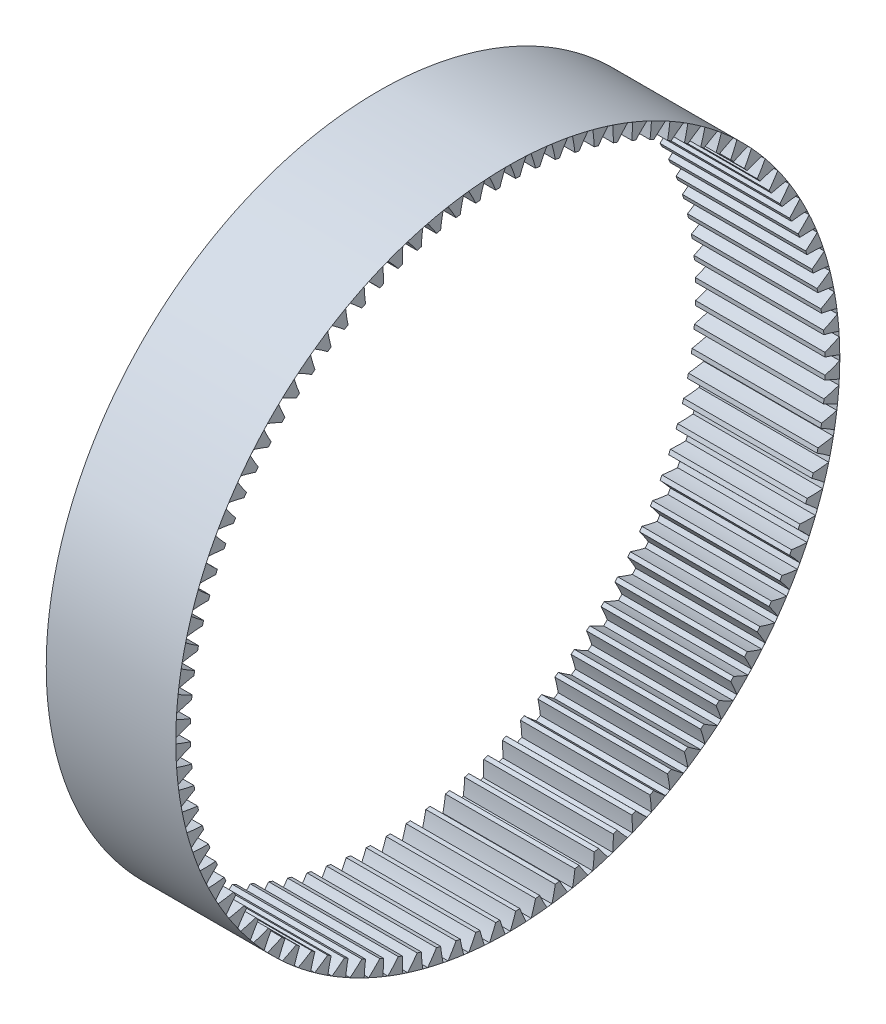
SolidWorks part; units mm, degrees
ref_plane "Plane1" through (0, 0, 0) normal (0, 0, 1) x (1, 0, 0)
ref_plane "Plane2" through (0, 0, 0) normal (0, 1, 0) x (1, 0, 0)
ref_plane "Plane3" through (0, 0, 0) normal (1, 0, 0) x (0, 0, -1)
other "Configuration Table"
sketch "HoldingSke" plane through (0, 0, 0) normal (0, 1, 0) x (1, 0, 0)
  line L0 (0, 0) -> (-0.0579, -0.3283)
  line L1 (-15, 0) -> (100, 0) construction
  line L2 (0, 0) -> (-2.1039, 2.3779)
  line L3 (0, 0) -> (-11.863, 4.5341)
  line L4 (0, 0) -> (-1.4996, 8.5048)
  line L5 (0, 0) -> (-23.7986, -8.8762)
  line L6 (0, 0) -> (-10.5278, -7.1032)
  line L7 (-2.1039, 2.3779) -> (3.3635, 27.1825)
  line L8 (-76.2, 5.3779) -> (-54.61, 5.3779)
  line L9 (-71.009, 38.7566) -> (-53.1078, 45.2721)
  line L10 (-76.2, 71.12) -> (104.1128, 71.12)
  line L11 (0, 0) -> (-60, 0)
  line L12 (-76.2, 101.6) -> (-76.093, 101.6)
  line L13 (24.9733, 27.94) -> (52.9518, 28.4284)
  line L14 (24.9733, 27.94) -> (24.9743, 27.94)
  line L15 (24.9733, 27.94) -> (100.4006, 29.5858)
  circle A0 centre (0, 0) radius 12.5
  circle A1 centre (0, 0) radius 12.7
  circle A2 centre (0, 0) radius 12.7
  dimension "MHD" = 25.4
  dimension "Hub_dia" = 25.4
  dimension "Diameter" = 25
  dimension "Num_teeth" = 100
  dimension "Pitch" = 0.3333
  dimension "Overall_len" = 25.4
  dimension "Show_teeth" = 100
  dimension "Thickness" = 12.7
  dimension "OAL" = 25.4001
  dimension "T_dim" = 21.59
  dimension "Ap" = 20
  dimension "H" = 19.05
  dimension "Pitch_radius" = 180.3128
  dimension "Width" = 60
  dimension "Backlash" = 0.107
  dimension "Addendum_fac" = 1
  dimension "Dedendum_fac" = 1.25
  dimension "Clearance_fac" = 0.25
  dimension "Dedendum_add" = 0.001
  dimension "Module" = 3
sketch "BasProSke" plane through (0, 0, 0) normal (0, 1, 0) x (1, 0, 0)
  line L0 (-10, 0) -> (60, 0) construction
  line L1 (0, 147) -> (0, 153.7764)
  line L2 (0, 147) -> (60, 147)
  line L3 (60, 147) -> (60, 153.7764)
  line L4 (60, 153.7764) -> (0, 153.7764)
  dimension "Thickness" = 60
  dimension "Diameter" = 307.5528
  dimension "Inside_diameter" = 294
revolve "Base-Revolve" add sketch "BasProSke" angle 360 about L0
sketch "TooCutSke" plane through (0, 0, 0) normal (1, 0, 0) x (0, 0, -1)
  line L3 (2.6236, 149.9771) -> (2.6236, 53.6633) construction
  line L4 (0, 0) -> (0, 59.563) construction
  line L5 (0, 0) -> (-2.1462, 68.2938) construction
  line L6 (-68.0184, 124.7836) -> (33.8394, 127.9846) construction
  circle A0 centre (0, 0) radius 150 construction
  circle A1 centre (0, 0) radius 153.751 construction
  circle A2 centre (0, 0) radius 126.8585 construction
  circle A3 centre (0, 0) radius 146.9746 construction
  arc A4 (3.6374, 146.9296) -> (1.1636, 153.7466) centre (-68.0184, 124.7836) ccw
  arc A5 (3.6374, 146.9296) -> (-3.6374, 146.9296) centre (0, 0) ccw
  arc A6 (1.1636, 153.7466) -> (-1.1636, 153.7466) centre (0, 0) ccw
  arc A7 (-1.1636, 153.7466) -> (-3.6374, 146.9296) centre (68.0184, 124.7836) ccw
  dimension "Pitch_dia" = 300
  dimension "Base_dia" = 253.717
  dimension "Root_dia" = 307.502
  dimension "Overcut_dia" = 293.9492
  dimension "Flank_rad" = 75
  dimension "Half_ang" = 1.8
  dimension "Half_CT" = 2.6236
extrude "ToothCut" cut sketch "TooCutSke" along normal through all
fillet "Breaks" [suppressed] radius 0.3
fillet "RootFillets" [suppressed] radius 0.751
pattern_circular "TeethCuts" count 100 every 3.6 about axis through (-10, 0, 0) along (1, 0, 0) of "RootFillets", "Breaks", "ToothCut"
equation "' \"Module@HoldingSke\" = 6.35"
equation "' \"Num_teeth@HoldingSke\" = 24"
equation "' \"Ap@HoldingSke\" =  14.5"
equation "' \"Ap@HoldingSke\" = 14.5"
equation "' \"Width@HoldingSke\" = 12"
equation "' \"Diameter@HoldingSke\" = 8 * 25.4"
equation "' \"Show_teeth@HoldingSke\" = 100"
equation "' \"Backlash@HoldingSke\" = 0.009 * 25.4"
equation "' \"Addendum_fac@HoldingSke\" = 1.0"
equation "' \"Dedendum_fac@HoldingSke\" = 1.25"
equation "' \"Dedendum_add@HoldingSke\" = 0.00005 * 25.4"
equation "' \"Clearance_fac@HoldingSke\" = 0.25"
equation "\"Pitch@HoldingSke\" = 1 / \"Module@HoldingSke\" "
equation "\"Overcut_dia@TooCutSke\" = (\"Num_teeth@HoldingSke\" - 2 * \"Addendum_fac@HoldingSke\") / \"Pitch@HoldingSke\" - 0.002 * 25.4"
equation "\"Pitch_dia@TooCutSke\" = \"Num_teeth@HoldingSke\" / \"Pitch@HoldingSke\""
equation "\"Base_dia@TooCutSke\" = \"Num_teeth@HoldingSke\" / \"Pitch@HoldingSke\" * cos((\"Ap@HoldingSke\"  * 3.14159265 / 180)) * 0.90"
equation "\"Root_dia@TooCutSke\" = \"Num_teeth@HoldingSke\"  / \"Pitch@HoldingSke\" + 2 *  \"Dedendum_fac@HoldingSke\"/ \"Pitch@HoldingSke\" + \"Dedendum_add@HoldingSke\" * 2"
equation "\"Half_ang@TooCutSke\" = 180 / \"Num_teeth@HoldingSke\""
equation "\"Half_CT@TooCutSke\" = \"Num_teeth@HoldingSke\" / \"Pitch@HoldingSke\" * sin((3.14159265 / 2 / \"Num_teeth@HoldingSke\")) / 2 + 10 * \"Backlash@HoldingSke\" / 4"
equation "\"Flank_rad@TooCutSke\" = \"Num_teeth@HoldingSke\" / \"Pitch@HoldingSke\" / 4"
equation "\"Radius@RootFillets\"= \"Clearance_fac@HoldingSke\" / \"Pitch@HoldingSke\" + \"Dedendum_add@HoldingSke\""
equation "\"Break_rad@Breaks\" = 0.02 / \"Pitch@HoldingSke\" * 5"
equation "\"Num_teeth@TeethCuts\" = int( \"Show_teeth@HoldingSke\" ) + 1"
equation "\"Num_teeth@TeethCuts\" = ((sgn( \"Num_teeth@TeethCuts\" - \"Num_teeth@HoldingSke\" )-1)*( \"Num_teeth@TeethCuts\" - \"Num_teeth@HoldingSke\" ))/-2+ \"Num_teeth@HoldingSke\""
equation "\"Num_teeth@TeethCuts\" = ((sgn( \"Num_teeth@TeethCuts\" - 2.0)+1)*( \"Num_teeth@TeethCuts\" - 2.0))/2 +2.0"
equation "\"Angle@TeethCuts\" = 360.0 / \"Num_teeth@HoldingSke\""
equation "\"Diameter@BasProSke\" = \"Num_teeth@HoldingSke\"  / \"Pitch@HoldingSke\" + 2 *  \"Dedendum_fac@HoldingSke\"/ \"Pitch@HoldingSke\" + \"Dedendum_add@HoldingSke\" * 2 + 0.002 * 25.4"
equation "\"Diameter@BasProSke\" = ((sgn( \"Diameter@BasProSke\"  - \"Diameter@HoldingSke\" )+1)*( \"Diameter@BasProSke\"  - \"Diameter@HoldingSke\" ))/2 + \"Diameter@HoldingSke\""
equation "\"Inside_diameter@BasProSke\" =  (\"Num_teeth@HoldingSke\" - 2 * \"Addendum_fac@HoldingSke\") / \"Pitch@HoldingSke\" "
equation "\"Thickness@BasProSke\"  = \"Width@HoldingSke\""
